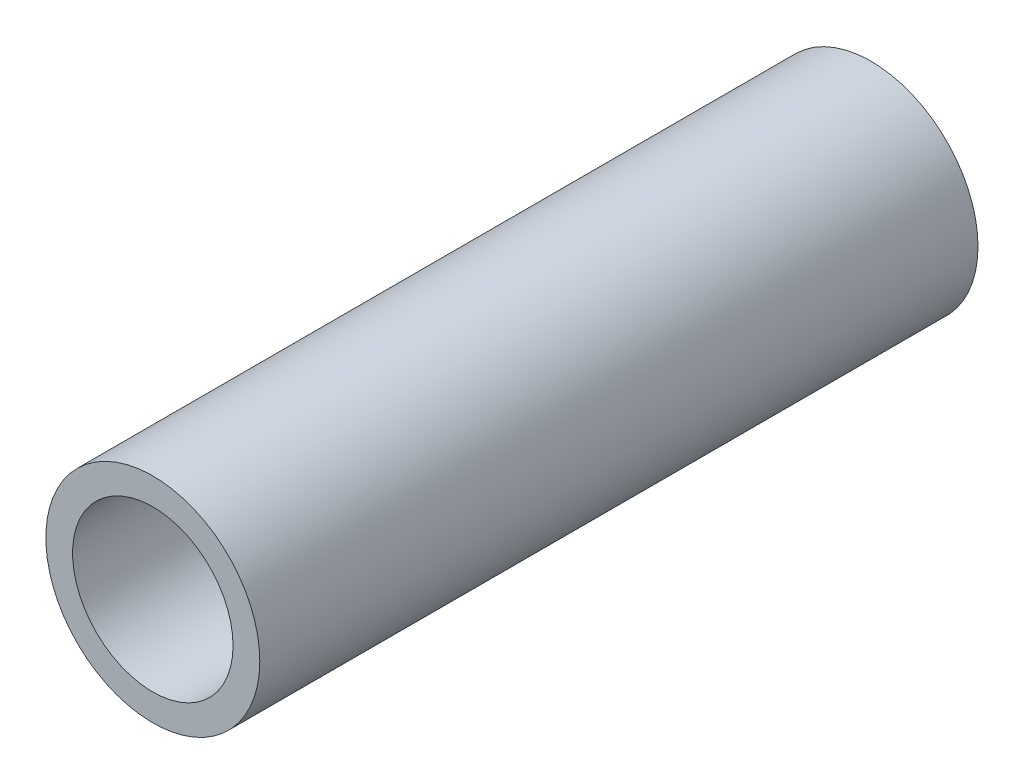
SolidWorks part; units mm, degrees
ref_plane "Front Plane" through (0, 0, 0) normal (0, 0, 1) x (1, 0, 0)
ref_plane "Top Plane" through (0, 0, 0) normal (0, 1, 0) x (1, 0, 0)
ref_plane "Right Plane" through (0, 0, 0) normal (1, 0, 0) x (0, 0, -1)
sketch "Sketch1" plane through (0, 0, 0) normal (0, 0, 1) x (1, 0, 0)
  circle A0 centre (0, 0) radius 3.15
  circle A1 centre (0, 0) radius 4.2
  dimension "D1" = 6.3
  dimension "D2" = 8.4
extrude "Boss-Extrude1" add sketch "Sketch1" along normal blind 28.2
